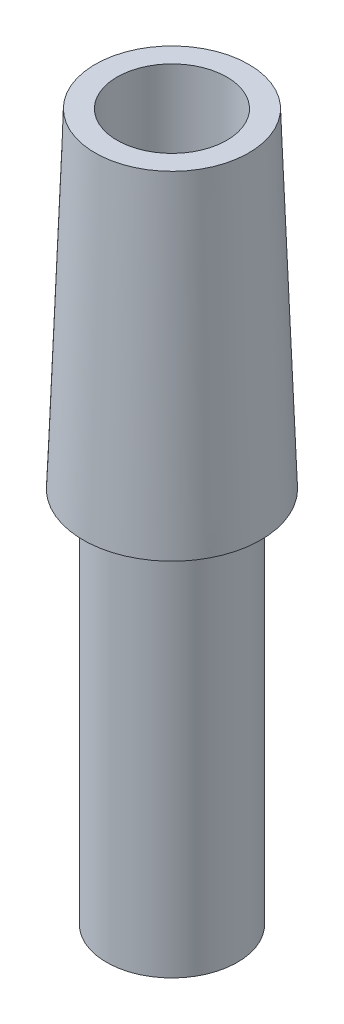
SolidWorks part; units mm, degrees
ref_plane "Piano frontale" through (0, 0, 0) normal (0, 0, 1) x (1, 0, 0)
ref_plane "Piano superiore" through (0, 0, 0) normal (0, 1, 0) x (1, 0, 0)
ref_plane "Piano destro" through (0, 0, 0) normal (1, 0, 0) x (0, 0, -1)
sketch "Schizzo1" plane through (0, 0, 0) normal (0, 0, 1) x (1, 0, 0)
  line L0 (0, 0) -> (0, 42.1267) construction
  line L1 (1.485, 0) -> (1.485, 18.8)
  line L2 (1.485, 18.8) -> (2.5, 18.8)
  line L3 (3.5, 32.2) -> (4.05, 17.2)
  line L4 (4.05, 17.2) -> (2.985, 17.2)
  line L5 (2.985, 17.2) -> (2.985, 0)
  line L6 (2.985, 0) -> (1.485, 0)
  line L7 (2.5, 18.8) -> (2.5, 32.2)
  line L8 (2.5, 32.2) -> (3.5, 32.2)
  dimension "D1" = 5.97
  dimension "D2" = 7
  dimension "D3" = 8.1
  dimension "D4" = 15
  dimension "D5" = 32.2
  dimension "D6" = 1.5
  dimension "D7" = 1
  dimension "D8" = 13.4
revolve "Rivoluzione1" add sketch "Schizzo1" angle 360 about L0
